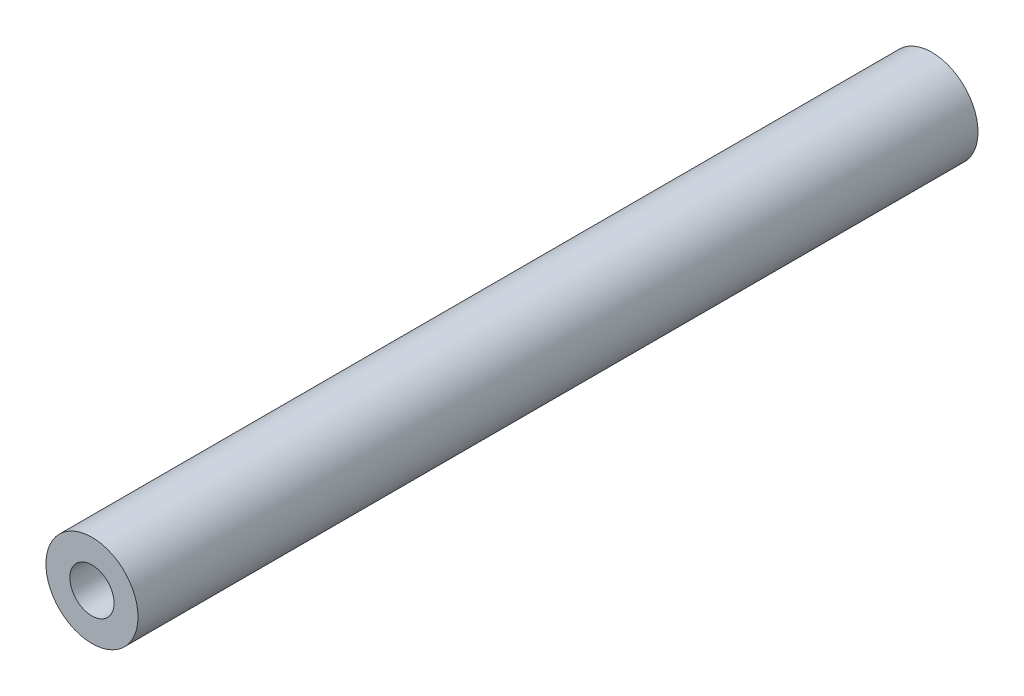
SolidWorks part; units mm, degrees
ref_plane "Front Plane" through (0, 0, 0) normal (0, 0, 1) x (1, 0, 0)
ref_plane "Top Plane" through (0, 0, 0) normal (0, 1, 0) x (1, 0, 0)
ref_plane "Right Plane" through (0, 0, 0) normal (1, 0, 0) x (0, 0, -1)
sketch "Sketch1" plane through (0, 0, 0) normal (0, 0, 1) x (1, 0, 0)
  circle A0 centre (0, 0) radius 3.175
  circle A1 centre (0, 0) radius 1.524
extrude "Boss-Extrude1" add sketch "Sketch1" along normal blind 57.912
